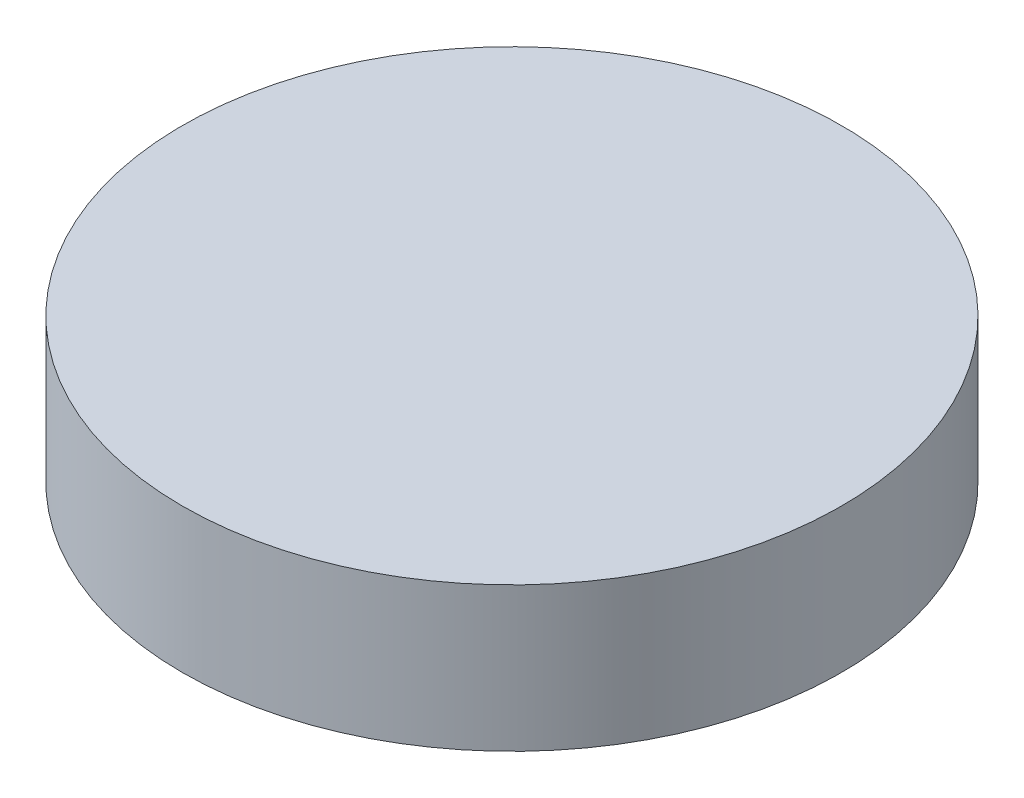
SolidWorks part; units mm, degrees
ref_plane "Front Plane" through (0, 0, 0) normal (0, 0, 1) x (1, 0, 0)
ref_plane "Top Plane" through (0, 0, 0) normal (0, 1, 0) x (1, 0, 0)
ref_plane "Right Plane" through (0, 0, 0) normal (1, 0, 0) x (0, 0, -1)
sketch "Sketch1" plane through (0, 0, 0) normal (0, 1, 0) x (1, 0, 0)
  circle A0 centre (0, 0) radius 50.8
  dimension "D1" = 101.6
extrude "Boss-Extrude1" add sketch "Sketch1" along normal blind 22.225
